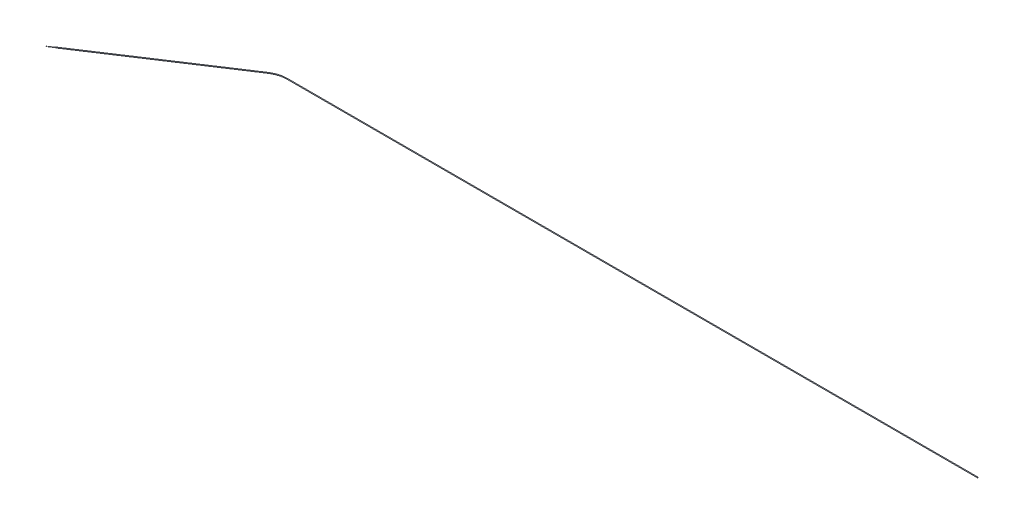
SolidWorks part; units mm, degrees
ref_plane "Front Plane" through (0, 0, 0) normal (0, 0, 1) x (1, 0, 0)
ref_plane "Top Plane" through (0, 0, 0) normal (0, 1, 0) x (1, 0, 0)
ref_plane "Right Plane" through (0, 0, 0) normal (1, 0, 0) x (0, 0, -1)
sketch "Sketch2" plane through (0, 0, 0) normal (0, 1, 0) x (1, 0, 0)
  line L0 (0, 20) -> (500, 20)
  line L1 (-10.9805, 16.7161) -> (-103.7551, -44.2254)
  arc A0 (0, 20) -> (-10.9805, 16.7161) centre (0, 0) ccw
  dimension "D1" = 20
  dimension "D2" = 500
  dimension "D3" = 111
  dimension "D4" = 33.3
sweep "Sweep1" add path "Sketch2" circular profile diameter 0.5 parameters "D3"=0.5
sketch "Sketch6" plane through (-92.7746, 0, 60.9415) normal (-0.8358, 0, 0.549) x (0.549, 0, 0.8358)
  circle A0 centre (-20, 0) radius 0.1
  dimension "D1" = 0.2
extrude "Boss-Extrude1" add sketch "Sketch6" along normal blind 5
